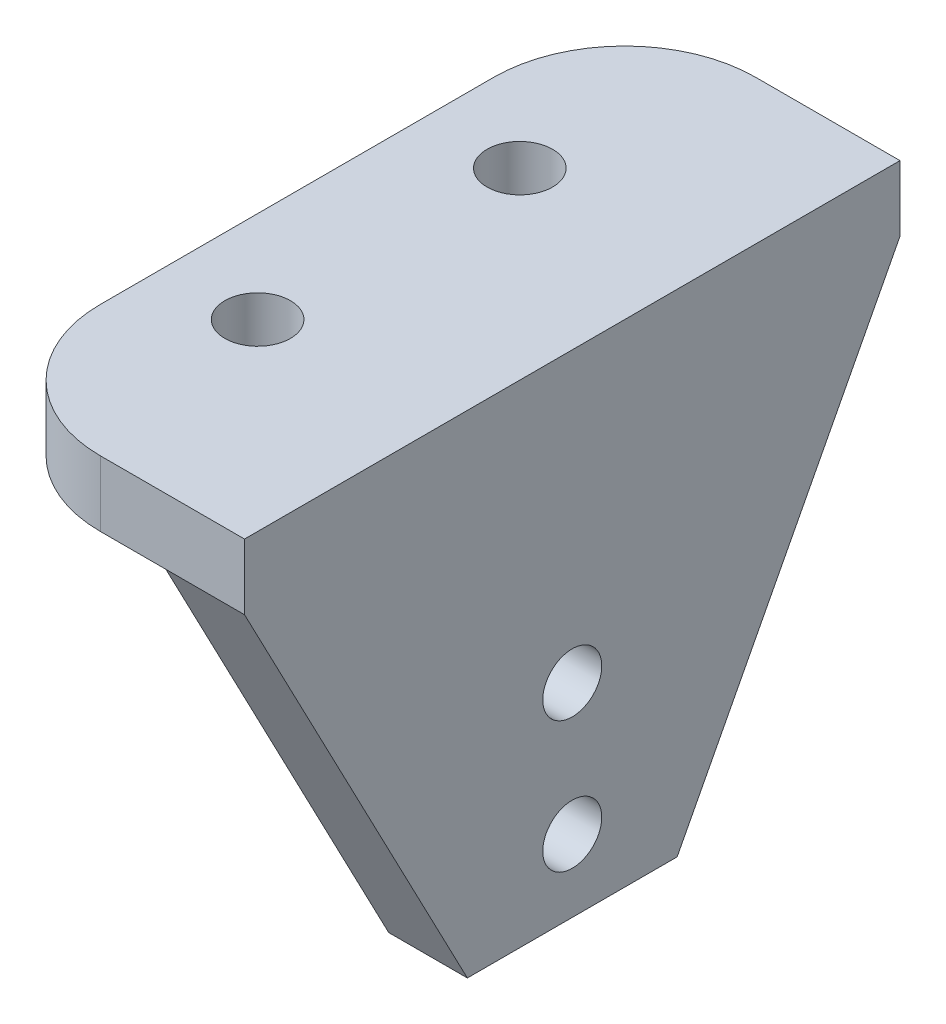
SolidWorks part; units mm, degrees
ref_plane "Plano frontal" through (0, 0, 0) normal (0, 0, 1) x (1, 0, 0)
ref_plane "Plano superior" through (0, 0, 0) normal (0, 1, 0) x (1, 0, 0)
ref_plane "Plano direito" through (0, 0, 0) normal (1, 0, 0) x (0, 0, -1)
sketch "Esboço1" plane through (0, 0, 0) normal (0, 1, 0) x (1, 0, 0)
  line L1 (0, 0) -> (15, 0)
  line L2 (0, 0) -> (0, 50)
  line L3 (0, 50) -> (15, 50)
  line L4 (15, 0) -> (15, 50)
  dimension "D1" = 50
  dimension "D2" = 15
extrude "Ressalto-extrusão1" add sketch "Esboço1" along normal blind 5
sketch "Esboço2" plane through (0, 5, 0) normal (0, 1, 0) x (1, 0, 0)
  line L0 (0, 25) -> (15, 25) construction
  line L1 (0, 50) -> (0, 0) construction
  line L2 (15, 0) -> (15, 50) construction
  line L3 (7, 50) -> (7, 0) construction
  line L6 (15, 50) -> (0, 50) construction
  line L7 (0, 0) -> (15, 0) construction
  circle A0 centre (7, 35) radius 2.5
  circle A1 centre (7, 15) radius 2.5
  dimension "D3" = 5
  dimension "D1" = 10
  dimension "D2" = 10
  dimension "D4" = 8
extrude "Corte-extrusão1" cut sketch "Esboço2" against normal through all
fillet "Filete1" radius 10 2 edges at (0, 2.5, 0) (0, 2.5, -50)
sketch "Esboço3" plane through (15, 0, 0) normal (1, 0, 0) x (0, 0, -1)
  line L6 (25, 5) -> (25, -32.5) construction
  line L7 (0, 5) -> (50, 5) construction
  line L8 (50, 5) -> (0, 5)
  line L9 (0, 5) -> (0, 0)
  line L10 (0, 0) -> (17, -32.5)
  line L11 (17, -32.5) -> (33, -32.5)
  line L12 (50, 0) -> (33, -32.5)
  line L13 (50, 5) -> (50, 0)
  dimension "D1" = 37.5
  dimension "D2" = 8
extrude "Ressalto-extrusão2" add sketch "Esboço3" along normal blind 6
hole_wizard "Rebaixo para parafuso com cabeça redonda de M41" positions "Esboço5" profile "Esboço6" counterbore size "M4" standard "ISO" end condition through all
sketch "Esboço5" plane through (15, 0, 0) normal (-1, 0, 0) x (0, 0, 1)
  line L0 (-17, -32.5) -> (-33, -32.5) construction
  line L1 (-25, -32.5) -> (-25, 5) construction
  line L2 (-40, 5) -> (-10, 5) construction
  point P0 (-25, -27)
  point P2 (-25, -17)
  dimension "D1" = 5.5
  dimension "D2" = 10
sketch "Esboço6" plane through (15, -27, -25) normal (0, 1, 0) x (0, 0, 1)
  line L0 (0, 0) -> (0, 6)
  line L1 (0, 6) -> (2.25, 6)
  line L3 (2.25, 6) -> (2.25, 2.6)
  line L4 (4, 2.6) -> (2.25, 2.6)
  line L5 (4, 2.6) -> (4, 0.025)
  line L6 (4, 0.025) -> (4.025, 0)
  line L7 (4.025, 0) -> (0, 0)
  line L8 (-4, 0.025) -> (-4.025, 0) construction
  line L11 (0, -6.35) -> (0, 107.95) construction
  dimension "Thru Hole Dia." = 4.5
  dimension "Thru Hole Depth" = 6
  dimension "C'Bore Dia." = 8
  dimension "C'Bore Depth" = 2.6
  dimension "Near C'Sink Dia." = 8.05
  dimension "Near C'Sink Angle" = 90
